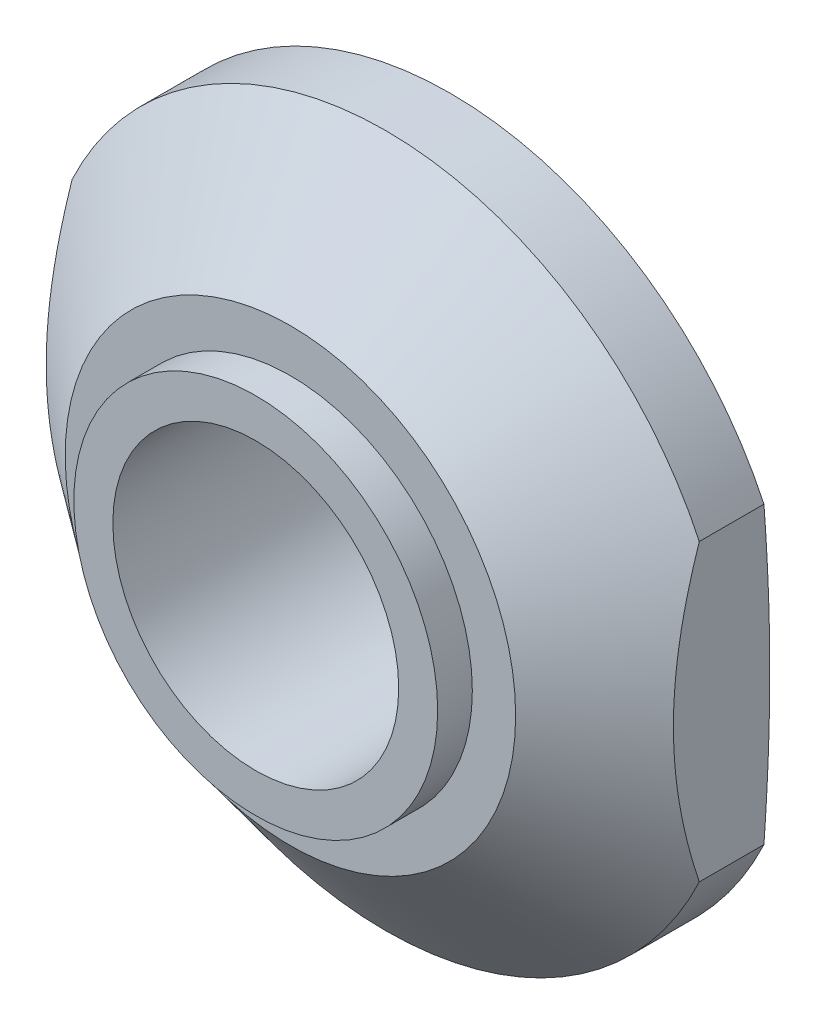
SolidWorks part; units mm, degrees
material "4140 H-T"
ref_plane "Front Plane" through (0, 0, 0) normal (0, 0, 1) x (1, 0, 0)
ref_plane "Top Plane" through (0, 0, 0) normal (0, 1, 0) x (1, 0, 0)
ref_plane "Right Plane" through (0, 0, 0) normal (1, 0, 0) x (0, 0, -1)
sketch "Sketch1" plane through (0, 0, 0) normal (1, 0, 0) x (0, 0, -1)
  line L0 (0, 0) -> (8.7817, 0) construction
  line L1 (0, 4.125) -> (0, 5.25)
  line L2 (1, 5.25) -> (1, 6.5)
  line L3 (3.75, 10) -> (5.6151, 10)
  line L4 (6.1, 5.175) -> (7, 5.175)
  line L5 (7, 4.125) -> (0, 4.125)
  line L6 (7, 5.175) -> (7, 4.125)
  line L7 (6.1, 7.25) -> (6.1, 5.175)
  line L8 (0, 5.25) -> (1, 5.25)
  line L9 (6.1, 7.25) -> (5.6151, 10)
  line L10 (1, 6.5) -> (3.75, 10)
  dimension "D1" = 20
  dimension "D2" = 8.25
  dimension "D3" = 1
  dimension "D4" = 13
  dimension "D5" = 6.1
  dimension "D6" = 14.5
  dimension "D7" = 10.5
  dimension "D8" = 10.35
  dimension "D9" = 7
  dimension "D10" = 3.75
  dimension "D11" = 10
revolve "Revolve1" add sketch "Sketch1" angle 360 about L0
cosmetic thread "Cosmetic Thread1" parameters "D2"=9
sketch "Sketch2" plane through (0, 0, -6.1) normal (0, 0, -1) x (-1, 0, 0)
  line L0 (0, 0) -> (0, 10.6119) construction
  line L1 (0, 0) -> (14.3103, 0) construction
  line L2 (9.05, 8.1832) -> (12.1023, 8.1832)
  line L3 (9.05, 8.1832) -> (9.05, -8.1832)
  line L4 (9.05, -8.1832) -> (12.1023, -8.1832)
  line L5 (12.1023, 8.1832) -> (12.1023, -8.1832)
  line L6 (-12.1023, 8.1832) -> (-12.1023, -8.1832)
  line L7 (-9.05, -8.1832) -> (-12.1023, -8.1832)
  line L8 (-9.05, 8.1832) -> (-9.05, -8.1832)
  line L9 (-9.05, 8.1832) -> (-12.1023, 8.1832)
  dimension "D1" = 24.2046
  dimension "D2" = 16.3664
  dimension "D3" = 18.1
extrude "Cut-Extrude1" cut sketch "Sketch2" against normal up to next
